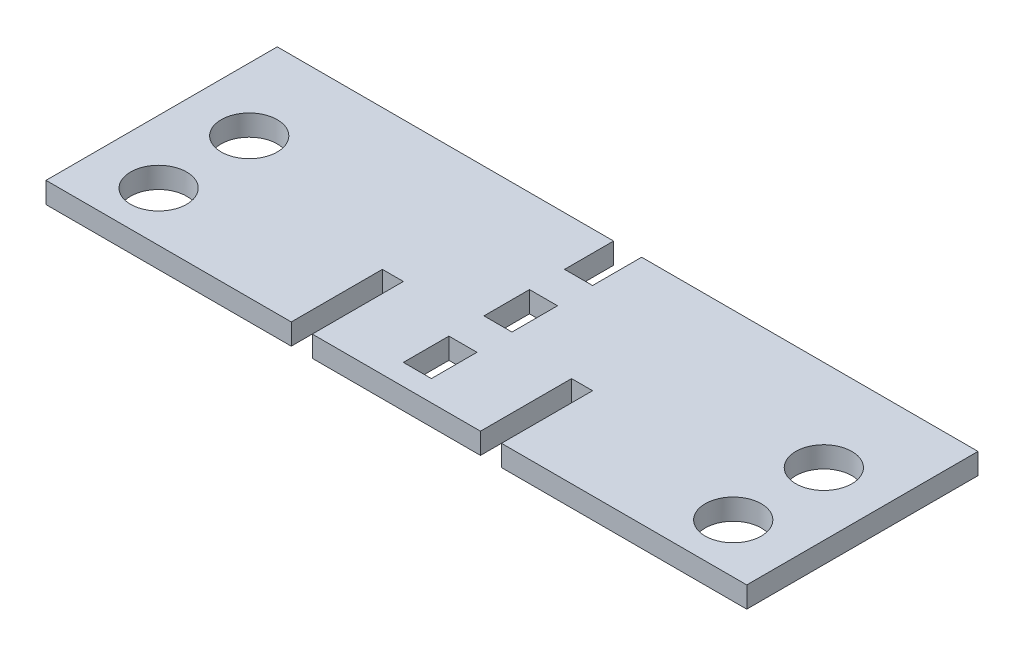
SolidWorks part; units mm, degrees
ref_plane "Спереди" through (0, 0, 0) normal (0, 0, 1) x (1, 0, 0)
ref_plane "Сверху" through (0, 0, 0) normal (0, 1, 0) x (1, 0, 0)
ref_plane "Справа" through (0, 0, 0) normal (1, 0, 0) x (0, 0, -1)
other "Configuration Table"
sketch "Эскиз1" plane through (0, 0, 0) normal (0, 1, 0) x (1, 0, 0)
  line L0 (2, 10) -> (50, 10)
  line L1 (-50, -10) -> (50, -10)
  line L2 (-50, -10) -> (-50, 10)
  line L3 (-50, 10) -> (-2, 10)
  line L4 (50, -10) -> (50, 10)
  line L5 (-50, -10) -> (50, 10) construction
  line L6 (-50, 10) -> (50, -10) construction
  line L8 (-2, 10) -> (-2, 6.3274)
  line L9 (-2, 6.3274) -> (2, 6.3274)
  line L10 (2, 10) -> (2, 6.3274)
  line L11 (0, -11.5536) -> (0, 11.5536) construction
  circle A0 centre (-41, -3) radius 4
  circle A1 centre (41, -3) radius 4
  point P0 (0, 0)
  point P15 (0, 0)
  dimension "D6" = 8
  dimension "D5" = 9
  dimension "D7" = 7
  dimension "D1" = 20
  dimension "D2" = 100
  dimension "D3" = 4
  dimension "D4" = 48
extrude "Бобышка-Вытянуть1" add sketch "Эскиз1" along normal blind 3
sketch "Эскиз2" plane through (0, 0, -6.3274) normal (0, 0, -1) x (-1, 0, 0)
  line L4 (-2, 0) -> (2, 0)
  line L5 (2, 0) -> (2, 3)
  line L6 (2, 3) -> (-2, 3)
  line L7 (-2, 3) -> (-2, 0)
  line L8 (-2, 0) -> (2, 0)
  line L9 (2, 0) -> (2, 3)
  line L10 (2, 3) -> (-2, 3)
  line L11 (-2, 3) -> (-2, 0)
  dimension "D1" = 0
extrude "Вырез-Вытянуть1" cut sketch "Эскиз2" against normal blind 3.33
sketch "Эскиз3" plane through (0, 3, 0) normal (0, 1, 0) x (1, 0, 0)
  line L0 (-50, -10) -> (50, -10) construction
  line L1 (-12, -23) -> (12, -23)
  line L2 (-12, -23) -> (-12, -10)
  line L3 (-12, -10) -> (12, -10)
  line L4 (12, -23) -> (12, -10)
  line L5 (-12, -23) -> (12, -10) construction
  line L6 (-12, -10) -> (12, -23) construction
  line L8 (-50, 10) -> (-50, -10) construction
  point P0 (0, -16.5)
  dimension "D1" = 24
  dimension "D2" = 13
  dimension "D3" = 50
extrude "Бобышка-Вытянуть2" add sketch "Эскиз3" against normal up to surface (3 mm away) up to face at (0, 0, -3.2493)
sketch "Эскиз4" plane through (0, 3, 0) normal (0, 1, 0) x (1, 0, 0)
  line L0 (-12, -10) -> (-12, -23) construction
  line L1 (-50, -10) -> (-15, -10)
  line L2 (-50, -10) -> (-50, -23)
  line L3 (-50, -23) -> (-15, -23)
  line L4 (-15, -10) -> (-15, -23)
  line L5 (50, -10) -> (15, -10)
  line L6 (50, -10) -> (50, -23)
  line L7 (50, -23) -> (15, -23)
  line L8 (15, -10) -> (15, -23)
  line L9 (12, -23) -> (12, -10) construction
  dimension "D1" = 3
  dimension "D2" = 3
extrude "Бобышка-Вытянуть3" add sketch "Эскиз4" against normal up to surface (3 mm away) up to face at (0, 0, 3.3338)
sketch "Эскиз5" plane through (0, 3, 0) normal (0, 1, 0) x (1, 0, 0)
  circle A0 centre (-41, -15.9275) radius 4
  circle A1 centre (41, -15.9275) radius 4
  dimension "D1" = 8
  dimension "D2" = 8
extrude "Вырез-Вытянуть2" cut sketch "Эскиз5" against normal blind 25
sketch "Эскиз6" plane through (0, 3, 0) normal (0, 1, 0) x (1, 0, 0)
  line L0 (-2, 2.9974) -> (2, 2.9974) construction
  line L1 (-2, -2.0026) -> (2, -2.0026)
  line L2 (-2, -2.0026) -> (-2, -8.5026)
  line L3 (-2, -8.5026) -> (2, -8.5026)
  line L4 (2, -2.0026) -> (2, -8.5026)
  line L6 (-2, -13.5026) -> (2, -13.5026)
  line L7 (-2, -13.5026) -> (-2, -20.0026)
  line L8 (-2, -20.0026) -> (2, -20.0026)
  line L9 (2, -13.5026) -> (2, -20.0026)
  point P10 (0, -13.5026)
  point P11 (0, -8.5026)
  dimension "D1" = 5
  dimension "D2" = 11.5
  dimension "D3" = 5
  dimension "D4" = 11.5
extrude "Вырез-Вытянуть3" cut sketch "Эскиз6" against normal blind 25
